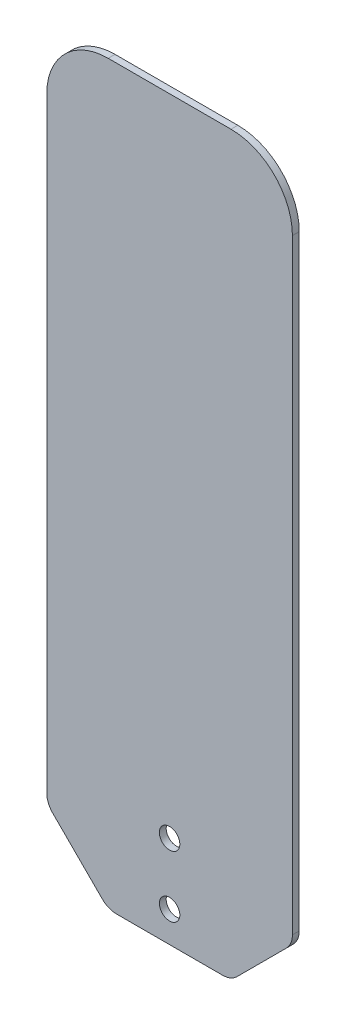
SolidWorks part; units mm, degrees
ref_plane "Alzado" through (0, 0, 0) normal (0, 0, 1) x (1, 0, 0)
ref_plane "Planta" through (0, 0, 0) normal (0, 1, 0) x (1, 0, 0)
ref_plane "Vista lateral" through (0, 0, 0) normal (1, 0, 0) x (0, 0, -1)
sketch "Model" plane through (0, 0, 0) normal (0, 0, 1) x (1, 0, 0)
  line L0 (91.3925, 168.7619) -> (106.9072, 168.7619)
  line L1 (117.1499, 179.0045) -> (117.1499, 267.7645)
  line L2 (108.1499, 276.7645) -> (90.1499, 276.7645)
  line L3 (81.1499, 267.7645) -> (81.1499, 179.0045)
  line L4 (89.2712, 169.6406) -> (82.0286, 176.8832)
  line L5 (109.0286, 169.6406) -> (116.2712, 176.8832)
  circle A0 centre (99.1499, 173.2619) radius 1.5
  arc A1 (117.1499, 267.7645) -> (108.1499, 276.7645) centre (108.1499, 267.7645) ccw
  arc A2 (90.1499, 276.7645) -> (81.1499, 267.7645) centre (90.1499, 267.7645) ccw
  circle A3 centre (99.1499, 182.2619) radius 1.5
  arc A4 (81.1499, 179.0045) -> (82.0286, 176.8832) centre (84.1499, 179.0045) ccw
  arc A5 (116.2712, 176.8832) -> (117.1499, 179.0045) centre (114.1499, 179.0045) ccw
  arc A6 (106.9072, 168.7619) -> (109.0286, 169.6406) centre (106.9072, 171.7619) ccw
  arc A7 (89.2712, 169.6406) -> (91.3925, 168.7619) centre (91.3925, 171.7619) ccw
extrude "Saliente-Extruir1" add sketch "Model" along normal blind 1
